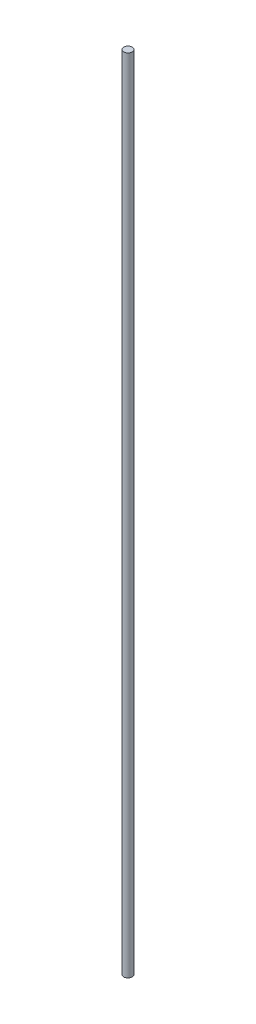
SolidWorks part; units mm, degrees
ref_plane "正面" through (0, 0, 0) normal (0, 0, 1) x (1, 0, 0)
ref_plane "平面" through (0, 0, 0) normal (0, 1, 0) x (1, 0, 0)
ref_plane "右側面" through (0, 0, 0) normal (1, 0, 0) x (0, 0, -1)
sketch "ｽｹｯﾁ1" plane through (0, 0, 0) normal (0, 1, 0) x (1, 0, 0)
  circle A0 centre (0, 0) radius 8
  dimension "D1" = 16
extrude "ﾎﾞｽ - 押し出し1" add sketch "ｽｹｯﾁ1" along normal blind 1500
